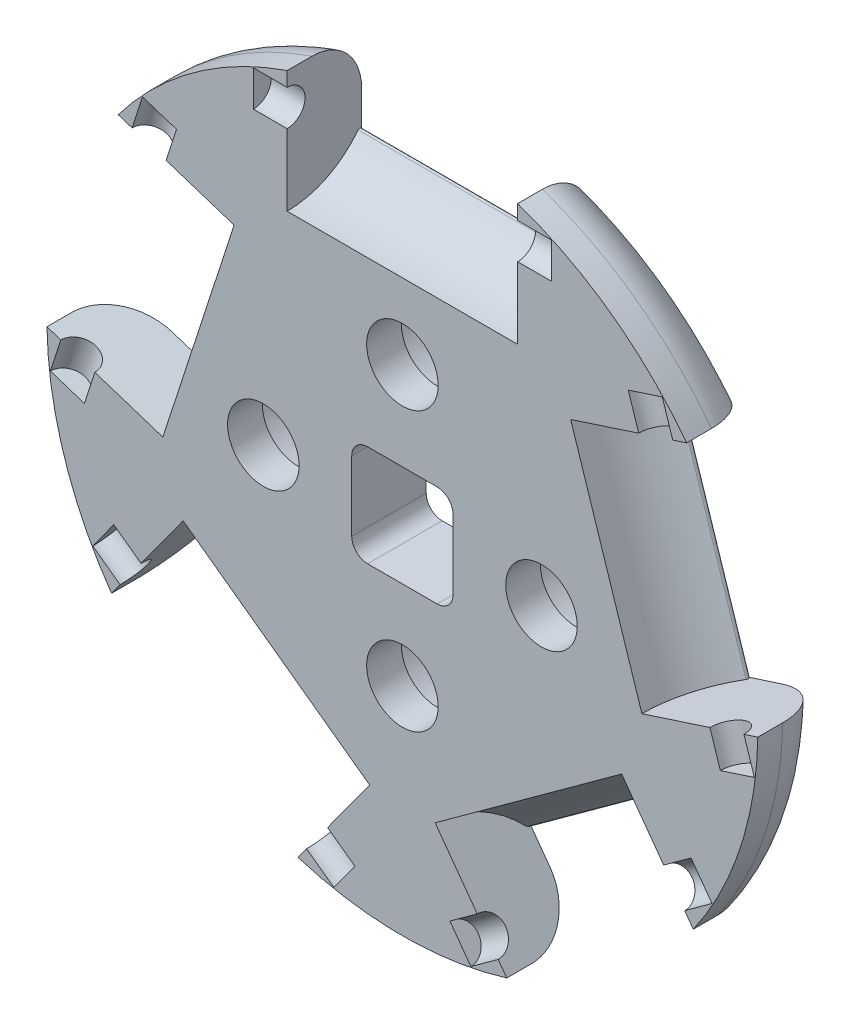
SolidWorks part; units mm, degrees
other "Markup1"
sketch "Sketch8" plane through (32.7336, 32.7336, 0) normal (0.5701, 0.1846, 0.8006) x (0.8043, 0.0736, -0.5897)
ref_plane "Front Plane" through (0, 0, 0) normal (0, 0, 1) x (1, 0, 0)
ref_plane "Top Plane" through (0, 0, 0) normal (0, 1, 0) x (1, 0, 0)
ref_plane "Right Plane" through (0, 0, 0) normal (1, 0, 0) x (0, 0, -1)
sketch "Sketch1" plane through (0, 0, 0) normal (0, 0, 1) x (1, 0, 0)
  circle A0 centre (0, 0) radius 22.7203
  dimension "D1" = 45.4406
extrude "Boss-Extrude2" add sketch "Sketch1" against normal blind 4.7625
fillet "Fillet1" radius 3.175 1 edges at (22.7203, 0, -4.7625)
sketch "Sketch2" plane through (0, 0, 0) normal (0, 0, 1) x (1, 0, 0)
  line L1 (-12.7, 22.7203) -> (12.7, 22.7203) construction
  line L2 (-7.366, 23.9903) -> (7.366, 23.9903)
  line L3 (-7.366, 23.9903) -> (-7.366, 13.5763)
  line L4 (-7.366, 13.5763) -> (7.366, 13.5763)
  line L5 (7.366, 23.9903) -> (7.366, 13.5763)
  line L6 (-7.366, 23.9903) -> (7.366, 13.5763) construction
  line L7 (-7.366, 13.5763) -> (7.366, 23.9903) construction
  line L35 (0, 0) -> (0, 22.7203) construction
  circle A1 centre (0, 0) radius 22.7203 construction
  point P10 (0, 18.7833)
  circle M7 centre (0, 0) radius 22.7203
  dimension "D1" = 14.732
  dimension "D2" = 10.414
  dimension "D3" = 1.27
  dimension "D4" = 25.4
extrude "Cut-Extrude2" cut sketch "Sketch2" against normal blind 12.7 contours L5 L3 L4 M7
pattern_circular "CirPattern1" count 5 over 360 about axis through (0, 0, 0) along (0, 0, 1) of "Cut-Extrude2"
ref_plane "Plane1" through (0, 0, 0) normal (1, 0, 0) x (0, 0, -1)
sketch "Sketch4" plane through (0, 0, 0) normal (1, 0, 0) x (0, 0, -1)
  line L0 (4.7625, 13.5763) -> (0, 13.5763) construction
  circle A0 centre (0, 19.4183) radius 1.143
  dimension "D1" = 2.286
  dimension "D2" = 5.842
extrude "Cut-Extrude4" cut sketch "Sketch4" against normal mid plane 19.05
pattern_circular "CirPattern2" count 5 over 360 about axis through (0, 0, 0) along (0, 0, 1) of "Cut-Extrude4"
sketch "Sketch5" plane through (0, 0, 0) normal (0, 0, 1) x (1, 0, 0)
  line L1 (-3.2385, -3.2385) -> (3.2385, -3.2385)
  line L2 (-3.2385, -3.2385) -> (-3.2385, 3.2385)
  line L3 (-3.2385, 3.2385) -> (3.2385, 3.2385)
  line L4 (3.2385, -3.2385) -> (3.2385, 3.2385)
  line L5 (-3.2385, -3.2385) -> (3.2385, 3.2385) construction
  line L6 (-3.2385, 3.2385) -> (3.2385, -3.2385) construction
  point P0 (0, 0)
  dimension "D1" = 6.477
extrude "Cut-Extrude5" cut sketch "Sketch5" against normal through all
sketch "Sketch6" plane through (0, 0, -4.7625) normal (0, 0, -1) x (-1, 0, 0)
  line L1 (2.7411, 0) -> (-2.7411, 0) construction
  line L2 (0, 2.7411) -> (0, -2.7411) construction
  circle A0 centre (0, 8.89) radius 2.286
  circle A1 centre (8.89, 0) radius 2.286
  circle A2 centre (0, -8.89) radius 2.286
  circle A3 centre (-8.89, 0) radius 2.286
  dimension "D4" = 4.572
  dimension "D1" = 8.89
  dimension "D2" = 8.89
extrude "Cut-Extrude7" cut sketch "Sketch6" against normal through all
sketch "Sketch7" plane through (0, 0, -4.7625) normal (0, 0, -1) x (-1, 0, 0)
  circle A0 centre (-8.89, 0) radius 4.445
  circle A1 centre (8.89, 0) radius 4.445
  circle A2 centre (0, -8.89) radius 4.445
  circle A3 centre (0, 8.89) radius 4.445
  dimension "D2" = 8.89
extrude "Cut-Extrude8" cut sketch "Sketch7" against normal blind 2.54
sketch "Sketch10" plane through (7.366, 0, 0) normal (-1, 0, 0) x (0, 0, 1)
  line L0 (-4.7625, 18.1042) -> (-4.7625, 13.5763) construction
  line L1 (-4.7625, 13.5763) -> (0, 13.5763)
  line L2 (-4.7625, 13.5763) -> (-4.7625, 16.2592)
  line L4 (0, 13.5763) -> (0, 13.7033)
  arc A0 (-4.7625, 16.2592) -> (0, 13.7033) centre (0, 19.4183) ccw
  dimension "D1" = 11.43
  dimension "D2" = 4.7625
extrude "Boss-Extrude4" add sketch "Sketch10" along normal up to next
fillet "Fillet2" radius 0.127 1 edges at (0, 16.2592, -4.7625)
pattern_circular "CirPattern5" count 5 over 360 of "Boss-Extrude4", "Fillet2"
fillet "Fillet3" radius 1.016 4 edges at (3.2385, -3.2385, -2.3813) (3.2385, 3.2385, -2.3813) (-3.2385, 3.2385, -2.3813) (-3.2385, -3.2385, -2.3813)
